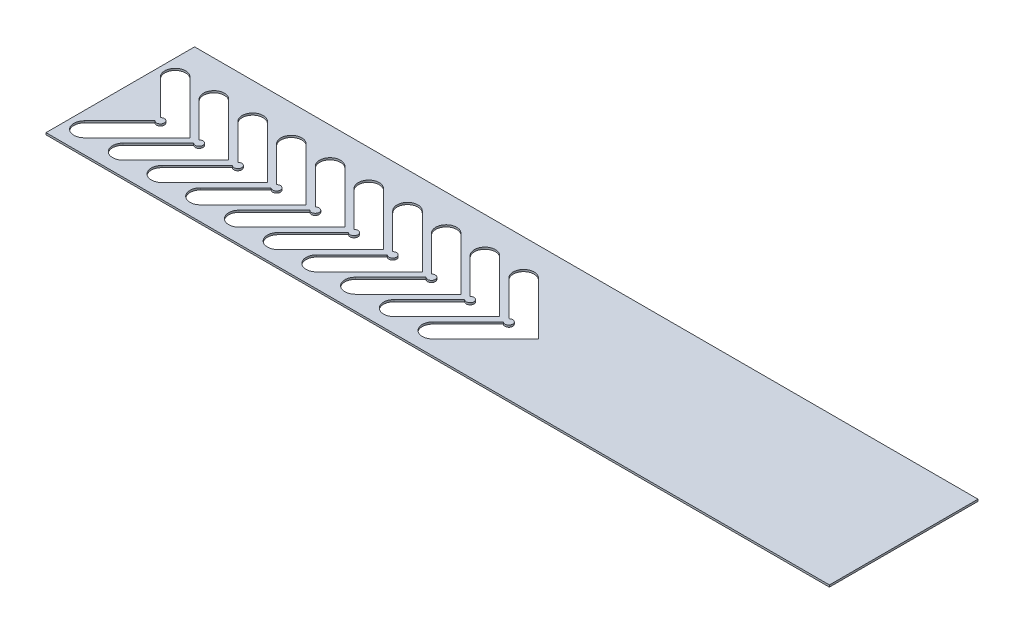
SolidWorks part; units mm, degrees
ref_plane "Front Plane" through (0, 0, 0) normal (0, 0, 1) x (1, 0, 0)
ref_plane "Top Plane" through (0, 0, 0) normal (0, 1, 0) x (1, 0, 0)
ref_plane "Right Plane" through (0, 0, 0) normal (1, 0, 0) x (0, 0, -1)
sketch "Sketch1" plane through (0, 0, 0) normal (0, 1, 0) x (1, 0, 0)
  line L0 (0, 0) -> (-42.2327, 0) construction
  line L1 (-36.9264, -17.438) -> (165.4316, -17.438)
  line L2 (-36.9264, -17.438) -> (-36.9264, 20.938)
  line L3 (-36.9264, 20.938) -> (165.4316, 20.938)
  line L4 (165.4316, -17.438) -> (165.4316, 20.938)
  line L5 (-34.6356, 9.8288) -> (-25.5139, 0.7071)
  line L6 (-25.5139, -0.7071) -> (-34.6356, -9.8288)
  line L7 (-30.8172, 13.6472) -> (-17.1701, 0)
  line L8 (-17.1701, 0) -> (-30.8172, -13.6472)
  line L9 (-20.8172, 13.6472) -> (-7.1701, 0)
  line L10 (-7.1701, 0) -> (-20.8172, -13.6472)
  line L11 (-34.6356, 9.8288) -> (-24.8068, 0) construction
  line L12 (-24.8068, 0) -> (-34.6356, -9.8288) construction
  line L13 (-15.5139, -0.7071) -> (-24.6356, -9.8288)
  line L14 (-24.6356, 9.8288) -> (-15.5139, 0.7071)
  line L15 (-10.8172, 13.6472) -> (2.8299, 0)
  line L16 (2.8299, 0) -> (-10.8172, -13.6472)
  line L17 (-5.5139, -0.7071) -> (-14.6356, -9.8288)
  line L18 (-14.6356, 9.8288) -> (-5.5139, 0.7071)
  line L19 (-0.8172, 13.6472) -> (12.8299, 0)
  line L20 (12.8299, 0) -> (-0.8172, -13.6472)
  line L21 (4.4861, -0.7071) -> (-4.6356, -9.8288)
  line L22 (-4.6356, 9.8288) -> (4.4861, 0.7071)
  line L23 (9.1828, 13.6472) -> (22.8299, 0)
  line L24 (22.8299, 0) -> (9.1828, -13.6472)
  line L25 (14.4861, -0.7071) -> (5.3644, -9.8288)
  line L26 (5.3644, 9.8288) -> (14.4861, 0.7071)
  line L27 (19.1828, 13.6472) -> (32.8299, 0)
  line L28 (32.8299, 0) -> (19.1828, -13.6472)
  line L29 (24.4861, -0.7071) -> (15.3644, -9.8288)
  line L30 (15.3644, 9.8288) -> (24.4861, 0.7071)
  line L31 (29.1828, 13.6472) -> (42.8299, 0)
  line L32 (42.8299, 0) -> (29.1828, -13.6472)
  line L33 (34.4861, -0.7071) -> (25.3644, -9.8288)
  line L34 (25.3644, 9.8288) -> (34.4861, 0.7071)
  line L35 (39.1828, 13.6472) -> (52.8299, 0)
  line L36 (52.8299, 0) -> (39.1828, -13.6472)
  line L37 (44.4861, -0.7071) -> (35.3644, -9.8288)
  line L38 (35.3644, 9.8288) -> (44.4861, 0.7071)
  line L39 (49.1828, 13.6472) -> (62.8299, 0)
  line L40 (62.8299, 0) -> (49.1828, -13.6472)
  line L41 (54.4861, -0.7071) -> (45.3644, -9.8288)
  line L42 (45.3644, 9.8288) -> (54.4861, 0.7071)
  line L43 (59.1828, 13.6472) -> (72.8299, 0)
  line L44 (72.8299, 0) -> (59.1828, -13.6472)
  line L45 (64.4861, -0.7071) -> (55.3644, -9.8288)
  line L46 (55.3644, 9.8288) -> (64.4861, 0.7071)
  line L47 (-30.2772, 14.438) -> (-35.4264, 14.438) construction
  line L48 (-35.4264, 14.438) -> (-35.4264, 7.8551) construction
  line L49 (-30.2772, -14.438) -> (-35.4264, -14.438) construction
  arc A0 (-34.6356, 9.8288) -> (-30.8172, 13.6472) centre (-32.7264, 11.738) cw
  arc A1 (-30.8172, -13.6472) -> (-34.6356, -9.8288) centre (-32.7264, -11.738) cw
  arc A2 (-25.5139, -0.7071) -> (-25.5139, 0.7071) centre (-24.8068, 0) ccw
  arc A3 (-20.8172, -13.6472) -> (-24.6356, -9.8288) centre (-22.7264, -11.738) cw
  arc A4 (-15.5139, -0.7071) -> (-15.5139, 0.7071) centre (-14.8068, 0) ccw
  arc A5 (-24.6356, 9.8288) -> (-20.8172, 13.6472) centre (-22.7264, 11.738) cw
  arc A6 (-10.8172, -13.6472) -> (-14.6356, -9.8288) centre (-12.7264, -11.738) cw
  arc A7 (-5.5139, -0.7071) -> (-5.5139, 0.7071) centre (-4.8068, 0) ccw
  arc A8 (-14.6356, 9.8288) -> (-10.8172, 13.6472) centre (-12.7264, 11.738) cw
  arc A9 (-0.8172, -13.6472) -> (-4.6356, -9.8288) centre (-2.7264, -11.738) cw
  arc A10 (4.4861, -0.7071) -> (4.4861, 0.7071) centre (5.1932, 0) ccw
  arc A11 (-4.6356, 9.8288) -> (-0.8172, 13.6472) centre (-2.7264, 11.738) cw
  arc A12 (9.1828, -13.6472) -> (5.3644, -9.8288) centre (7.2736, -11.738) cw
  arc A13 (14.4861, -0.7071) -> (14.4861, 0.7071) centre (15.1932, 0) ccw
  arc A14 (5.3644, 9.8288) -> (9.1828, 13.6472) centre (7.2736, 11.738) cw
  arc A15 (19.1828, -13.6472) -> (15.3644, -9.8288) centre (17.2736, -11.738) cw
  arc A16 (24.4861, -0.7071) -> (24.4861, 0.7071) centre (25.1932, 0) ccw
  arc A17 (15.3644, 9.8288) -> (19.1828, 13.6472) centre (17.2736, 11.738) cw
  arc A18 (29.1828, -13.6472) -> (25.3644, -9.8288) centre (27.2736, -11.738) cw
  arc A19 (34.4861, -0.7071) -> (34.4861, 0.7071) centre (35.1932, 0) ccw
  arc A20 (25.3644, 9.8288) -> (29.1828, 13.6472) centre (27.2736, 11.738) cw
  arc A21 (39.1828, -13.6472) -> (35.3644, -9.8288) centre (37.2736, -11.738) cw
  arc A22 (44.4861, -0.7071) -> (44.4861, 0.7071) centre (45.1932, 0) ccw
  arc A23 (35.3644, 9.8288) -> (39.1828, 13.6472) centre (37.2736, 11.738) cw
  arc A24 (49.1828, -13.6472) -> (45.3644, -9.8288) centre (47.2736, -11.738) cw
  arc A25 (54.4861, -0.7071) -> (54.4861, 0.7071) centre (55.1932, 0) ccw
  arc A26 (45.3644, 9.8288) -> (49.1828, 13.6472) centre (47.2736, 11.738) cw
  arc A27 (59.1828, -13.6472) -> (55.3644, -9.8288) centre (57.2736, -11.738) cw
  arc A28 (64.4861, -0.7071) -> (64.4861, 0.7071) centre (65.1932, 0) ccw
  arc A29 (55.3644, 9.8288) -> (59.1828, 13.6472) centre (57.2736, 11.738) cw
  point P17 (-17.1701, 0)
  dimension "D2" = 2
  dimension "D1" = 2.7
  dimension "D3" = 0
  dimension "D4" = 19.3
  dimension "D5" = 19.3
  dimension "D6" = 6.5
  dimension "D7" = 3
  dimension "D8" = 1.5
extrude "Boss-Extrude1" add sketch "Sketch1" along normal blind 0.5
